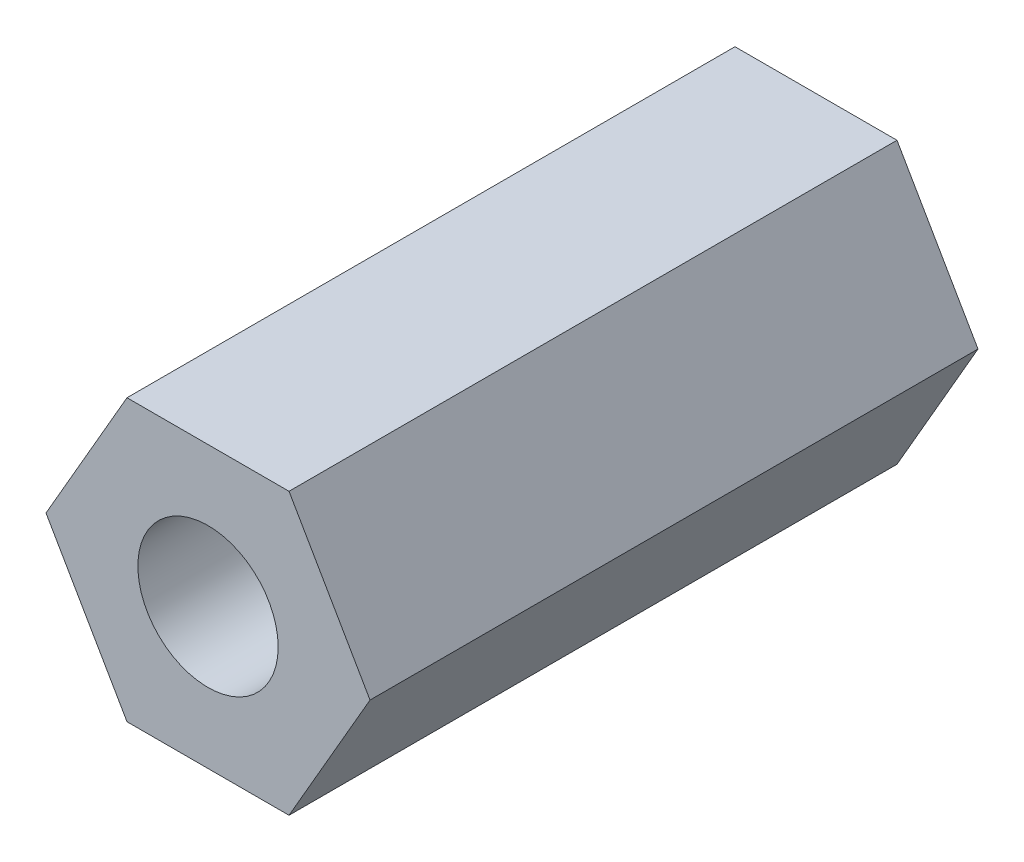
SolidWorks part; units mm, degrees
material "普通碳钢"
ref_plane "前视" through (0, 0, 0) normal (0, 0, 1) x (1, 0, 0)
ref_plane "上视" through (0, 0, 0) normal (0, 1, 0) x (1, 0, 0)
ref_plane "右视" through (0, 0, 0) normal (1, 0, 0) x (0, 0, -1)
sketch "草图1" plane through (0, 0, 0) normal (0, 0, 1) x (1, 0, 0)
  line L0 (0, 0) -> (3.4641, 0)
  line L1 (3.4641, 0) -> (5.1962, -3)
  line L2 (5.1962, -3) -> (3.4641, -6)
  line L3 (3.4641, -6) -> (0, -6)
  line L4 (0, -6) -> (-1.7321, -3)
  line L5 (-1.7321, -3) -> (0, 0)
  dimension "D1" = 6
  dimension "D2" = 6
extrude "凸台-拉伸1" add sketch "草图1" along normal blind 13
sketch "草图2" plane through (0, 0, 13) normal (0, 0, 1) x (1, 0, 0)
  line L0 (1.7321, 0) -> (1.7321, -6) construction
  line L1 (3.4641, 0) -> (0, 0) construction
  line L2 (0, -6) -> (3.4641, -6) construction
  line L3 (5.1962, -3) -> (-1.7321, -3) construction
  circle A0 centre (1.7321, -3) radius 1.5
extrude "切除-拉伸1" cut sketch "草图2" against normal through all
